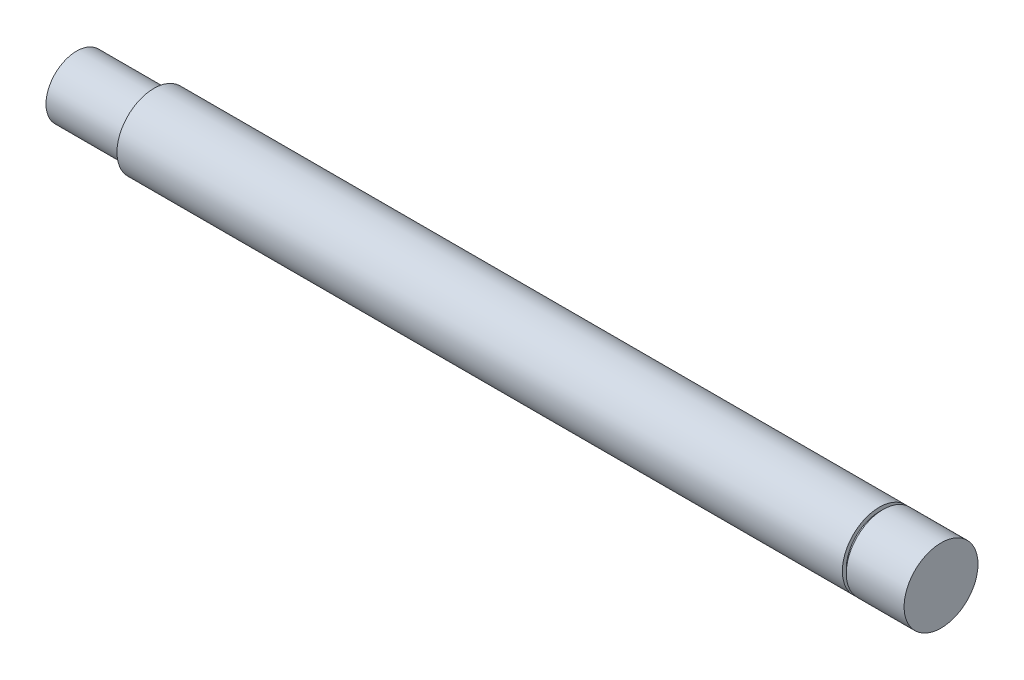
SolidWorks part; units mm, degrees
material "PW20:29:Sc:0:"
ref_plane "Front" through (0, 0, 0) normal (0, 0, 1) x (1, 0, 0)
ref_plane "Top" through (0, 0, 0) normal (0, 1, 0) x (1, 0, 0)
ref_plane "Right" through (0, 0, 0) normal (1, 0, 0) x (0, 0, -1)
sketch "Sketch1" plane through (0, 0, 0) normal (1, 0, 0) x (0, 0, -1)
  circle A0 centre (0, 0) radius 7.6
  dimension "D1" = 15.2
extrude "Base-Extrude" add sketch "Sketch1" along normal blind 177.8
ref_plane "Plane4" through (165.9, 0, 0) normal (1, 0, 0) x (0, 0, -1)
sketch "Sketch2" plane through (165.9, 0, 0) normal (1, 0, 0) x (0, 0, -1)
  circle A1 centre (0, 0) radius 6.8
  circle A2 centre (0, 0) radius 6.8
  circle A3 centre (0, 0) radius 7.6
  circle A4 centre (0, 0) radius 7.6
  dimension "D1" = 0.8
  dimension "D2" = 0
extrude "Cut-Extrude1" cut sketch "Sketch2" against normal blind 0.8
sketch "Sketch3" plane through (0, 0, 0) normal (-1, 0, 0) x (0, 0, 1)
  circle A0 centre (0, 0) radius 7.6 construction
  circle A1 centre (0, 0) radius 6.3
  circle A2 centre (0, 0) radius 6.3
  circle A3 centre (0, 0) radius 7.6
  dimension "D1" = 1.3
extrude "Cut-Extrude2" cut sketch "Sketch3" against normal blind 15.9
